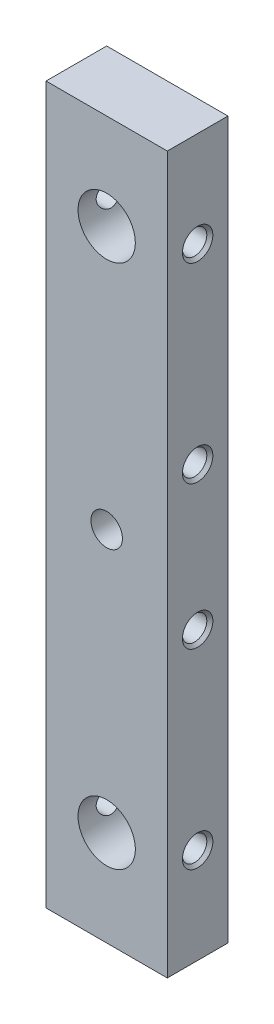
SolidWorks part; units mm, degrees
ref_plane "Alzado" through (0, 0, 0) normal (0, 0, 1) x (1, 0, 0)
ref_plane "Planta" through (0, 0, 0) normal (0, 1, 0) x (1, 0, 0)
ref_plane "Vista lateral" through (0, 0, 0) normal (1, 0, 0) x (0, 0, -1)
sketch "Croquis1" plane through (0, 0, 0) normal (0, 0, 1) x (1, 0, 0)
  line L0 (0, 0) -> (50000, 0) construction
  line L1 (-12.7, 75) -> (12.7, 75)
  line L2 (-12.7, 75) -> (-12.7, -75)
  line L3 (-12.7, -75) -> (12.7, -75)
  line L4 (12.7, 75) -> (12.7, -75)
  circle A0 centre (0, 55) radius 6
  circle A1 centre (0, -55) radius 6
  point P4 (0, 75)
  point P5 (-12.7, 0)
  dimension "D3" = 12
  dimension "D1" = 150
  dimension "D2" = 25.4
  dimension "D4" = 20
extrude "Saliente-Extruir1" add sketch "Croquis1" along normal mid plane 12.7
hole_wizard "Taladro roscado 1/4-201" positions "Croquis2" profile "Croquis3" tap size "1/4-20" standard "Ansi Inch" end condition through all
sketch "Croquis2" plane through (-12.7, 0, 0) normal (-1, 0, 0) x (0, 0, 1)
  line L1 (-4.3432, 0) -> (-3.4478, 0) construction
  point P0 (0, -15)
  point P3 (0, 15)
sketch "Croquis3" plane through (-12.7, -15, 0) normal (0, 1, 0) x (0, 0, 1)
  line L0 (0, 0) -> (0, 25.4)
  line L1 (0, 25.4) -> (3.1877, 25.4)
  line L2 (2.5527, 24.765) -> (2.5527, 0.635)
  line L3 (2.5527, 0.635) -> (3.1877, 0)
  line L5 (3.1877, 0) -> (0, 0)
  line L6 (-2.5527, 0.635) -> (-3.1877, 0) construction
  line L7 (3.1877, 25.4) -> (2.5527, 24.765)
  line L8 (-3.1877, 25.4) -> (-2.5527, 24.765) construction
  line L11 (0, -6.35) -> (0, 107.95) construction
  dimension "Diámetro de perforador para roscar hasta el siguiente" = 5.1054
  dimension "Profundidad de perforador para roscar hasta el siguiente" = 25.4
  dimension "Diámetro de avellanado cercano" = 6.3754
  dimension "Ángulo de avellanado cercano" = 90
  dimension "Diámetro de avellanado lejano" = 6.3754
  dimension "Ángulo de avellanado lejano" = 90
cosmetic thread "Rosca de taladro15" parameters "D1"=25.4, "D2"=6.35
cosmetic thread "Rosca de taladro16" parameters "D1"=25.4, "D2"=6.35
hole_wizard "Taladro roscado 1/4-202" positions "Croquis6" profile "Croquis7" tap size "1/4-20" standard "Ansi Inch" end condition through all
sketch "Croquis6" plane through (-12.7, 0, 0) normal (-1, 0, 0) x (0, 0, 1)
  line L0 (0, 0) -> (50000, 0) construction
  line L1 (6.35, -55) -> (-6.35, -55) construction
  point P0 (0, 55)
  point P2 (0, -55)
sketch "Croquis7" plane through (-12.7, 55, 0) normal (0, 1, 0) x (0, 0, 1)
  line L0 (0, 0) -> (0, 25.4)
  line L1 (0, 25.4) -> (3.1877, 25.4)
  line L2 (2.5527, 24.765) -> (2.5527, 0.635)
  line L3 (2.5527, 0.635) -> (3.1877, 0)
  line L5 (3.1877, 0) -> (0, 0)
  line L6 (-2.5527, 0.635) -> (-3.1877, 0) construction
  line L7 (3.1877, 25.4) -> (2.5527, 24.765)
  line L8 (-3.1877, 25.4) -> (-2.5527, 24.765) construction
  line L11 (0, -6.35) -> (0, 107.95) construction
  dimension "Diámetro de perforador para roscar hasta el siguiente" = 5.1054
  dimension "Profundidad de perforador para roscar hasta el siguiente" = 25.4
  dimension "Diámetro de avellanado cercano" = 6.3754
  dimension "Ángulo de avellanado cercano" = 90
  dimension "Diámetro de avellanado lejano" = 6.3754
  dimension "Ángulo de avellanado lejano" = 90
cosmetic thread "Rosca de taladro13" parameters "D2"=6.35
cosmetic thread "Rosca de taladro14" parameters "D2"=6.35
hole_wizard "Taladro roscado 3/8-161" [suppressed] positions "Croquis4" profile "Croquis5" tap size "3/8-16" standard "Ansi Inch"
sketch "Croquis4" plane through (0, 0, 6.35) normal (0, 0, 1) x (1, 0, 0)
  point P0 (0, 0)
sketch "Croquis5" plane through (0, 0, 6.35) normal (1, 0, 0) x (0, -1, 0)
  line L0 (0, 0) -> (0, 12.7)
  line L1 (0, 12.7) -> (5.3975, 12.7)
  line L2 (3.9687, 11.2712) -> (3.9687, 1.4287)
  line L3 (3.9687, 1.4287) -> (5.3975, 0)
  line L5 (5.3975, 0) -> (0, 0)
  line L6 (-3.9687, 1.4287) -> (-5.3975, 0) construction
  line L7 (5.3975, 12.7) -> (3.9687, 11.2712)
  line L8 (-5.3975, 12.7) -> (-3.9688, 11.2712) construction
  line L11 (0, -6.35) -> (0, 107.95) construction
  dimension "Diámetro de perforador para roscar hasta el siguiente" = 7.9375
  dimension "Profundidad de perforador para roscar hasta el siguiente" = 12.7
  dimension "Diámetro de avellanado cercano" = 10.795
  dimension "Ángulo de avellanado cercano" = 90
  dimension "Diámetro de avellanado lejano" = 10.795
  dimension "Ángulo de avellanado lejano" = 90
cosmetic thread "Rosca de taladro6" [suppressed] parameters "D2"=9.525
hole_wizard "Taladro de margen para 1" positions "Croquis8" profile "Croquis9" hole size "M6" standard "Ansi Metric" end condition through all
sketch "Croquis8" plane through (0, 0, 6.35) normal (0, 0, 1) x (1, 0, 0)
  point P0 (0, 0)
sketch "Croquis9" plane through (0, 0, 6.35) normal (1, 0, 0) x (0, -1, 0)
  line L0 (0, 0) -> (0, 12.7)
  line L1 (0, 12.7) -> (3.3, 12.7)
  line L2 (3.3, 12.7) -> (3.3, 0)
  line L5 (3.3, 0) -> (0, 0)
  line L11 (0, -6.35) -> (0, 107.95) construction
  dimension "Diámetro de taladro hasta el siguiente" = 6.6
  dimension "Profundidad de taladro hasta el siguiente" = 12.7
